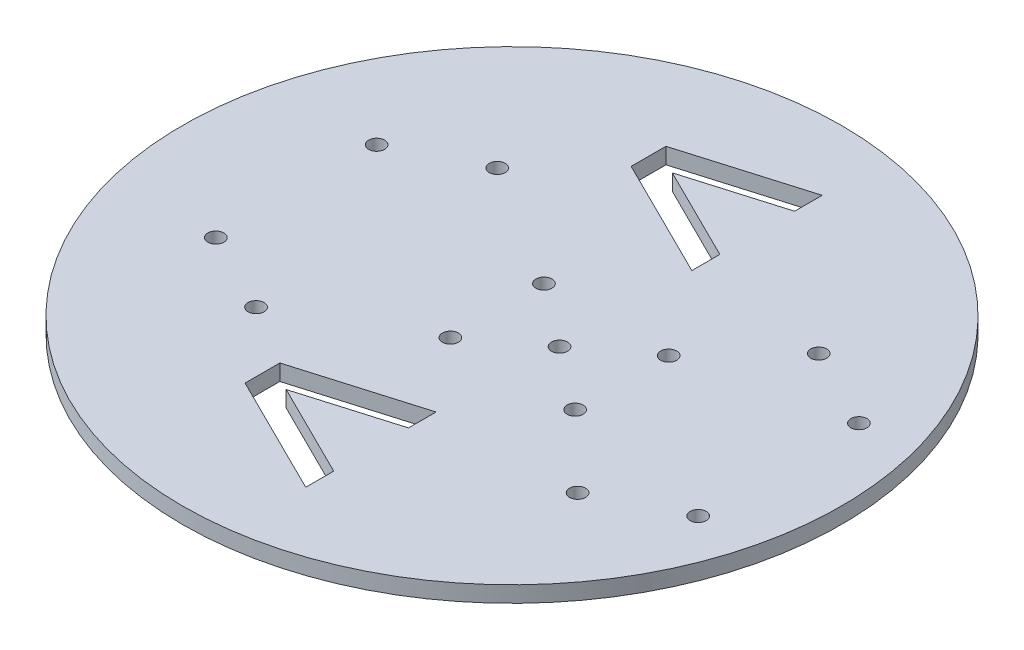
SolidWorks part; units mm, degrees
ref_plane "前视基准面" through (0, 0, 0) normal (0, 0, 1) x (1, 0, 0)
ref_plane "上视基准面" through (0, 0, 0) normal (0, 1, 0) x (1, 0, 0)
ref_plane "右视基准面" through (0, 0, 0) normal (1, 0, 0) x (0, 0, -1)
sketch "草图1" plane through (0, 0, 0) normal (0, 1, 0) x (1, 0, 0)
  line L7 (-150, -85) -> (-150, 85)
  line L14 (150, -40) -> (150, 40)
  line L62 (-2, 105) -> (30, 105)
  line L71 (150, 40) -> (138, 40)
  line L75 (123.4234, 70) -> (138, 40)
  line L97 (-163.3866, 0) -> (171.7808, 0) construction
  line L99 (-2, 105) -> (-25, 105)
  line L100 (56.4234, 85) -> (30, 105)
  line L102 (-25, 105) -> (-62, 85)
  line L104 (150, -40) -> (138, -40)
  line L108 (-2, -105) -> (-25, -105)
  line L111 (123.4234, -70) -> (138, -40)
  line L115 (-2, -105) -> (30, -105)
  line L135 (-25, -105) -> (-62, -85)
  line L138 (-150, 85) -> (-110, 85)
  line L141 (-150, -85) -> (-110, -85)
  line L142 (-62, 85) -> (-69, 85)
  line L145 (-62, -85) -> (-69, -85)
  line L146 (56.4234, 85) -> (67.4234, 85)
  line L148 (123.4234, 70) -> (108.6438, 70)
  line L149 (108.6438, 70) -> (108.6438, 85)
  line L150 (108.6438, -70) -> (108.6438, -85)
  line L151 (123.4234, -70) -> (108.6438, -70)
  line L153 (56.4234, -85) -> (67.4234, -85)
  line L154 (56.4234, -85) -> (30, -105)
  line L155 (108.6438, -85) -> (67.4234, -85)
  line L156 (-69, 85) -> (-110, 85)
  line L157 (67.4234, 85) -> (108.6438, 85)
  line L158 (-69, -85) -> (-110, -85)
extrude "上底板" add sketch "草图1" along normal mid plane 4
sketch "草图5" plane through (0, 0, 0) normal (0, 1, 0) x (1, 0, 0)
  line L0 (-6.3, 0) -> (-6.3, -46)
  line L1 (-71.4699, -46) -> (58.8301, -46)
  line L2 (-71.4699, -46) -> (-71.4699, 46)
  line L3 (-71.4699, 46) -> (58.8301, 46)
  line L4 (58.8301, 46) -> (58.8301, -46)
  line L5 (-71.4699, 46) -> (58.8301, -46)
  line L6 (58.8301, 46) -> (-71.4699, -46)
  circle A0 centre (-6.3199, 0) radius 92
  circle A1 centre (-6.3199, 0) radius 82
  circle A2 centre (-6.3, 0) radius 3
  point P0 (-6.3, 0)
extrude "防机械臂卡死圆环" cut sketch "草图5" against normal through all both and the other way through all contours A1 | A0
sketch "草图6" plane through (0, 0, 0) normal (0, 1, 0) x (1, 0, 0)
  line L0 (-13.745, -15.7478) -> (26.255, 14.2522) construction
  line L2 (-13.745, 14.2522) -> (-13.745, 10.8922) construction
  line L4 (-13.745, -15.7478) -> (-13.745, -12.3878) construction
  line L9 (-13.745, 14.2522) -> (6.255, -0.7478) construction
  line L10 (6.255, -0.7478) -> (26.255, -15.7478) construction
  line L12 (26.255, 14.2522) -> (26.255, 10.8922) construction
  line L13 (-13.745, 14.2522) -> (26.255, 14.2522) construction
  line L14 (-13.745, 14.2522) -> (-13.745, -15.7478) construction
  line L19 (-13.745, -15.7478) -> (26.255, -15.7478) construction
  line L20 (26.255, 14.2522) -> (26.255, -15.7478) construction
  line L21 (26.255, -15.7478) -> (26.255, -12.3878) construction
  line L22 (-13.745, 10.8922) -> (-9.265, 10.8922) construction
  line L23 (-13.745, -12.3878) -> (-9.265, -12.3878) construction
  line L24 (26.255, 10.8922) -> (21.775, 10.8922) construction
  line L25 (26.255, -12.3878) -> (21.775, -12.3878) construction
  circle A0 centre (6.255, -0.7478) radius 2
  circle A1 centre (-9.265, 10.8922) radius 2
  circle A2 centre (21.775, 10.8922) radius 2
  circle A3 centre (-9.265, -12.3878) radius 2
  circle A4 centre (21.775, -12.3878) radius 2
sketch "草图10" plane through (0, 0, 0) normal (0, 1, 0) x (1, 0, 0)
  line L0 (0, 0) -> (-130, 0) construction
  line L1 (0, 0) -> (115, 0) construction
  line L2 (-130, 0) -> (-130, 65)
  line L3 (-130, 0) -> (-130, -65)
  line L4 (115, 0) -> (115, 55)
  line L5 (115, 0) -> (115, -55)
  line L6 (0, 0) -> (-60, 0)
  line L7 (0, 0) -> (60, 0)
  line L8 (-60, 0) -> (-60, 20)
  line L9 (-60, 0) -> (-60, -20)
  line L10 (60, 0) -> (60, 20)
  line L11 (60, 0) -> (60, -20)
  circle A0 centre (-130, 65) radius 2
  circle A1 centre (-130, -65) radius 2
  circle A2 centre (115, 55) radius 2
  circle A3 centre (115, -55) radius 2
  circle A4 centre (-60, 20) radius 2
  circle A5 centre (-60, -20) radius 2
  circle A6 centre (60, 20) radius 2
  circle A7 centre (60, -20) radius 2
sketch "草图11" plane through (0, 0, 0) normal (0, 1, 0) x (1, 0, 0)
  line L14 (6.3252, 64.5351) -> (-23.6778, 55.6651)
  line L15 (-23.6778, 55.6651) -> (-23.6778, 47.0023)
  line L16 (-23.6778, 47.0023) -> (6.3252, 32.0963)
  line L17 (6.3252, 32.0963) -> (6.3252, 39.0619)
  line L18 (6.3252, 39.0619) -> (-17.162, 50.7307)
  line L19 (-17.162, 50.7307) -> (6.3252, 57.6745)
  line L20 (6.3252, 57.6745) -> (6.3252, 64.5351)
  line L21 (4.9816, -30.1901) -> (-25.0213, -39.0602)
  line L22 (-25.0213, -39.0602) -> (-25.0213, -47.723)
  line L23 (-25.0213, -47.723) -> (4.9816, -62.629)
  line L24 (4.9816, -62.629) -> (4.9816, -55.6633)
  line L25 (4.9816, -55.6633) -> (-18.5055, -43.9945)
  line L26 (-18.5055, -43.9945) -> (4.9816, -37.0508)
  line L27 (4.9816, -37.0508) -> (4.9816, -30.1901)
extrude "vv孔" cut sketch "草图11" against normal through all both and the other way through all contours L14 L15 L16 L17 L18 L19 L20 | L21 L22 L23 L24 L25 L26 L27
extrude "切除-拉伸7" cut sketch "草图10" against normal through all both and the other way through all contours A0 | A1 | A5 | A4 | A7 | A6 | A2 | A3
sketch "草图17" plane through (0, 0, 0) normal (0, 1, 0) x (1, 0, 0)
  line L1 (40, -30) -> (-40, -30)
  line L2 (40, -30) -> (40, 30)
  line L3 (40, 30) -> (-40, 30)
  line L4 (-40, -30) -> (-40, 30)
  line L5 (0, 30) -> (0, -30) construction
  line L6 (40, 0) -> (-40, 0) construction
  circle A0 centre (-40, 30) radius 2
  circle A1 centre (40, 30) radius 2
  circle A2 centre (-40, -30) radius 2
  circle A3 centre (40, -30) radius 2
  point P0 (0, 0)
extrude "切除-拉伸8" cut sketch "草图17" against normal through all both and the other way through all contours A0 | A1 | A3 | A2
extrude "切除-拉伸9" cut sketch "草图6" against normal through all both and the other way through all contours A4 | A1 | A3 | A0 | A2
sketch "草图18" plane through (0, 0, 0) normal (0, 1, 0) x (1, 0, 0)
  line L1 (26.255, -15.7478) -> (-13.745, -15.7478)
  line L2 (26.255, -15.7478) -> (26.255, 14.2522)
  line L3 (26.255, 14.2522) -> (-13.745, 14.2522)
  line L4 (-13.745, -15.7478) -> (-13.745, 14.2522)
  line L5 (6.255, 14.2522) -> (6.255, -15.7478) construction
  line L6 (26.255, -0.7478) -> (-13.745, -0.7478) construction
  point P0 (6.255, -0.7478)
  point P1 (6.255, -0.7478)
